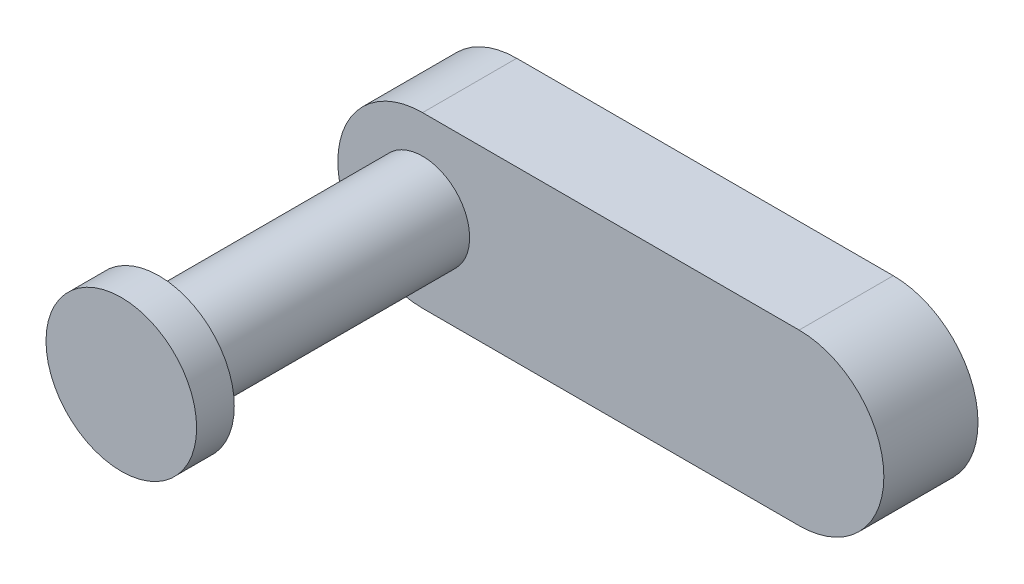
SolidWorks part; units mm, degrees
ref_plane "Front Plane" through (0, 0, 0) normal (0, 0, 1) x (1, 0, 0)
ref_plane "Top Plane" through (0, 0, 0) normal (0, 1, 0) x (1, 0, 0)
ref_plane "Right Plane" through (0, 0, 0) normal (1, 0, 0) x (0, 0, -1)
sketch "Sketch1" plane through (0, 0, 0) normal (0, 0, 1) x (1, 0, 0)
  line L0 (0, 5.715) -> (25.4, 5.715)
  line L2 (25.4, -5.715) -> (0, -5.715)
  arc A0 (0, -5.715) -> (0, 5.715) centre (0, 0) cw
  arc A1 (25.4, 5.715) -> (25.4, -5.715) centre (25.4, 0) cw
  dimension "D1" = 11.43
  dimension "D2" = 25.4
extrude "Boss-Extrude1" add sketch "Sketch1" along normal blind 6.35
sketch "Sketch2" plane through (0, 0, 6.35) normal (0, 0, 1) x (1, 0, 0)
  circle A0 centre (0, 0) radius 3.175
  dimension "D1" = 6.35
extrude "Boss-Extrude2" add sketch "Sketch2" along normal blind 20.32
sketch "Sketch3" plane through (0, 0, 26.67) normal (0, 0, 1) x (1, 0, 0)
  circle A0 centre (0, 0) radius 5.08
  dimension "D1" = 10.16
extrude "Boss-Extrude3" add sketch "Sketch3" against normal blind 2.54
